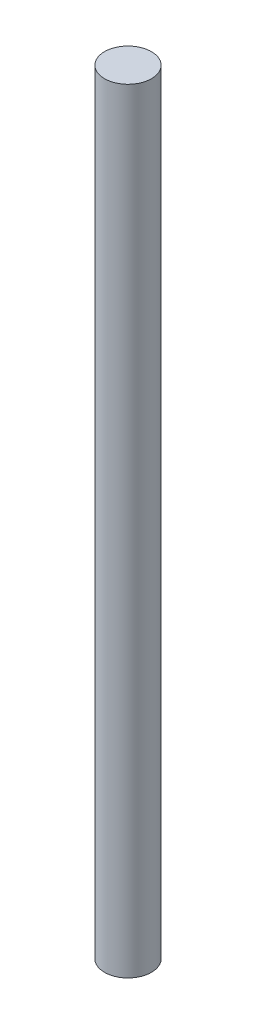
SolidWorks part; units mm, degrees
ref_plane "Front Plane" through (0, 0, 0) normal (0, 0, 1) x (1, 0, 0)
ref_plane "Top Plane" through (0, 0, 0) normal (0, 1, 0) x (1, 0, 0)
ref_plane "Right Plane" through (0, 0, 0) normal (1, 0, 0) x (0, 0, -1)
sketch "Sketch1" plane through (0, 0, 0) normal (0, 1, 0) x (1, 0, 0)
  circle A0 centre (0, 0) radius 5
  dimension "D1" = 10
extrude "Boss-Extrude1" add sketch "Sketch1" against normal blind 165
